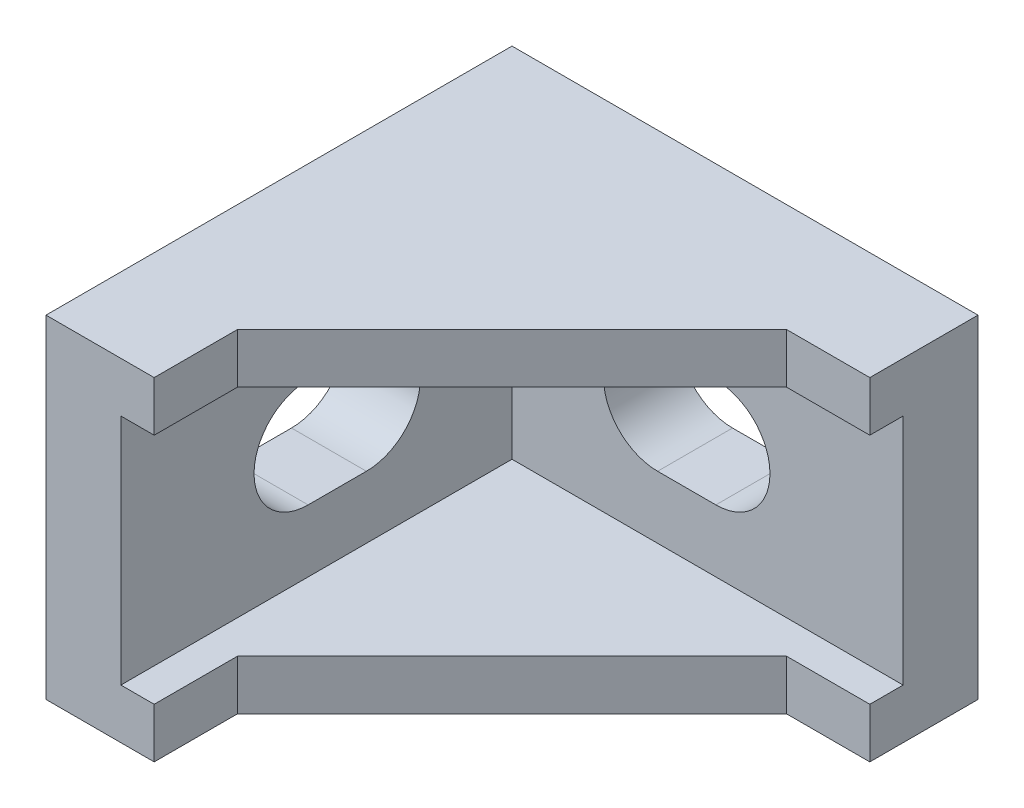
SolidWorks part; units mm, degrees
ref_plane "Front Plane" through (0, 0, 0) normal (0, 0, 1) x (1, 0, 0)
ref_plane "Top Plane" through (0, 0, 0) normal (0, 1, 0) x (1, 0, 0)
ref_plane "Right Plane" through (0, 0, 0) normal (1, 0, 0) x (0, 0, -1)
sketch "Sketch1" plane through (0, 0, 0) normal (0, 0, 1) x (1, 0, 0)
  line L0 (14, 0) -> (-14, 0) construction
  line L1 (-14, -10) -> (14, -10)
  line L2 (-14, -10) -> (-14, 10)
  line L3 (-14, 10) -> (14, 10)
  line L4 (14, -10) -> (14, 10)
  line L5 (-14, -10) -> (14, 10) construction
  line L6 (-14, 10) -> (14, -10) construction
  line L7 (1, 10) -> (1, -10) construction
  line L8 (-0.75, 0) -> (2.75, 0) construction
  line L9 (-0.75, 3.25) -> (2.75, 3.25)
  line L10 (-0.75, -3.25) -> (2.75, -3.25)
  arc A0 (-0.75, 3.25) -> (-0.75, -3.25) centre (-0.75, 0) ccw
  arc A1 (2.75, -3.25) -> (2.75, 3.25) centre (2.75, 0) ccw
  point P0 (0, 0)
  point P12 (1, 0)
  point P17 (6, 0)
  point P18 (-4, 0)
  dimension "D1" = 13
  dimension "D2" = 28
  dimension "D3" = 20
  dimension "D4" = 6.5
  dimension "D5" = 10
extrude "Boss-Extrude1" add sketch "Sketch1" along normal blind 4.5
sketch "Sketch3" plane through (0, -10, 0) normal (0, -1, 0) x (-1, 0, 0)
  line L0 (14, 0) -> (9.5, -4.5)
  line L1 (9.5, -4.5) -> (14, -4.5)
  line L2 (14, -4.5) -> (14, 0)
extrude "Cut-Extrude1" cut sketch "Sketch3" against normal blind 22
sketch "Sketch4" plane through (0, -10, 0) normal (0, -1, 0) x (-1, 0, 0)
  line L0 (-14, -4.5) -> (-14, -6.5)
  line L1 (-14, -6.5) -> (-9, -6.5)
  line L2 (-9, -6.5) -> (-0.75, -14.75)
  line L3 (-0.75, -14.75) -> (9.5, -4.5)
  line L4 (9.5, -4.5) -> (-14, -4.5)
  line L5 (14, 0) -> (9.5, -4.5) construction
  dimension "D1" = 2
  dimension "D2" = 5
extrude "Boss-Extrude3" add sketch "Sketch4" against normal blind 3
sketch "Sketch5" plane through (0, 0, 4.5) normal (0, 0, 1) x (1, 0, 0)
  line L0 (-9.5, 0) -> (14, 0) construction
  line L1 (-9.5, 10) -> (-9.5, -7) construction
  line L2 (14, -7) -> (14, 10) construction
ref_plane "Plane1" through (0, 0, 0) normal (0, -1, 0) x (1, 0, 0)
mirror "Mirror1" about plane through (0, 0, 0) normal (0, -1, 0) of "Boss-Extrude3"
mirror "Mirror2" about plane through (-14, 12, 0) normal (0.7071, 0, -0.7071) of bodies 105
